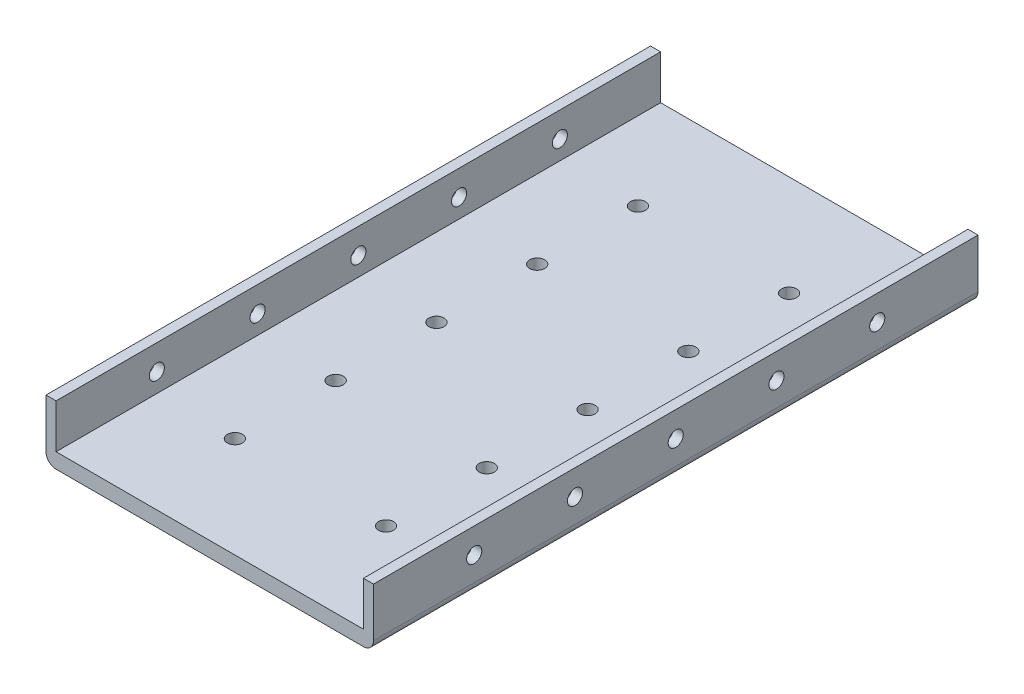
SolidWorks part; units mm, degrees
ref_plane "前视基准面" through (0, 0, 0) normal (0, 0, 1) x (1, 0, 0)
ref_plane "上视基准面" through (0, 0, 0) normal (0, 1, 0) x (1, 0, 0)
ref_plane "右视基准面" through (0, 0, 0) normal (1, 0, 0) x (0, 0, -1)
other "Configuration Table"
sketch "草图1" plane through (0, 0, 0) normal (0, 1, 0) x (1, 0, 0)
  line L1 (-32.5, -60) -> (32.5, -60)
  line L2 (-32.5, -60) -> (-32.5, 60)
  line L3 (-32.5, 60) -> (32.5, 60)
  line L4 (32.5, -60) -> (32.5, 60)
  line L5 (-32.5, -60) -> (32.5, 60) construction
  line L6 (-32.5, 60) -> (32.5, -60) construction
  point P0 (0, 0)
  dimension "D1" = 65
  dimension "D2" = 120
extrude "凸台-拉伸1" add sketch "草图1" along normal blind 3
sketch "草图2" plane through (0, 3, 0) normal (0, 1, 0) x (1, 0, 0)
  line L0 (-32.5, -60) -> (32.5, -60) construction
  line L1 (-32.5, 60) -> (-30.5, 60)
  line L2 (-32.5, 60) -> (-32.5, -60)
  line L3 (-32.5, -60) -> (-30.5, -60)
  line L4 (-30.5, 60) -> (-30.5, -60)
  line L5 (0, 82.6546) -> (0, -82.7207) construction
  line L6 (32.5, -60) -> (30.5, -60)
  line L7 (30.5, 60) -> (30.5, -60)
  line L8 (32.5, 60) -> (30.5, 60)
  line L9 (32.5, 60) -> (32.5, -60)
  dimension "D1" = 2
extrude "凸台-拉伸2" add sketch "草图2" along normal blind 8.75
fillet "圆角1" radius 2 2 edges at (32.5, 0, 0) (-32.5, 0, 0)
sketch "草图3" plane through (0, 0, 0) normal (0, -1, 0) x (1, 0, 0)
  line L0 (0, 79.3267) -> (0, -78.9704) construction
  line L3 (-30.5, 60) -> (30.5, 60) construction
  circle A0 centre (-15, 40) radius 1.5
  circle A1 centre (15, 40) radius 1.5
  circle A2 centre (-15, 20) radius 1.5
  circle A3 centre (15, 20) radius 1.5
  circle A4 centre (-15, 0) radius 1.5
  circle A5 centre (15, 0) radius 1.5
  circle A6 centre (-15, -20) radius 1.5
  circle A7 centre (15, -20) radius 1.5
  circle A8 centre (-15, -40) radius 1.5
  circle A9 centre (15, -40) radius 1.5
  dimension "D1" = 3
  dimension "D2" = 15
  dimension "D3" = 20
  dimension "D5" = 20
  dimension "D4" = 5
extrude "切除-拉伸1" cut sketch "草图3" against normal through all
sketch "草图4" plane through (-32.5, 0, 0) normal (-1, 0, 0) x (0, 0, 1)
  line L0 (0, 14.7504) -> (0, -4.1918) construction
  line L1 (-60, 11.75) -> (60, 11.75) construction
  line L3 (-60, 11.75) -> (-60, 2) construction
  circle A0 centre (0, 6.75) radius 1.5
  circle A1 centre (-20, 6.75) radius 1.5
  circle A2 centre (-40, 6.75) radius 1.5
  circle A3 centre (0, 6.75) radius 1.5
  circle A4 centre (-20, 6.75) radius 1.5
  circle A5 centre (20, 6.75) radius 1.5
  circle A6 centre (0, 6.75) radius 1.5
  circle A7 centre (20, 6.75) radius 1.5
  circle A8 centre (40, 6.75) radius 1.5
  dimension "D1" = 3
  dimension "D2" = 5
  dimension "D5" = 20
  dimension "D4" = 3
  dimension "D3" = 3
extrude "切除-拉伸2" cut sketch "草图4" against normal through all contours A2 | A1 | A0 | A5 | A8
